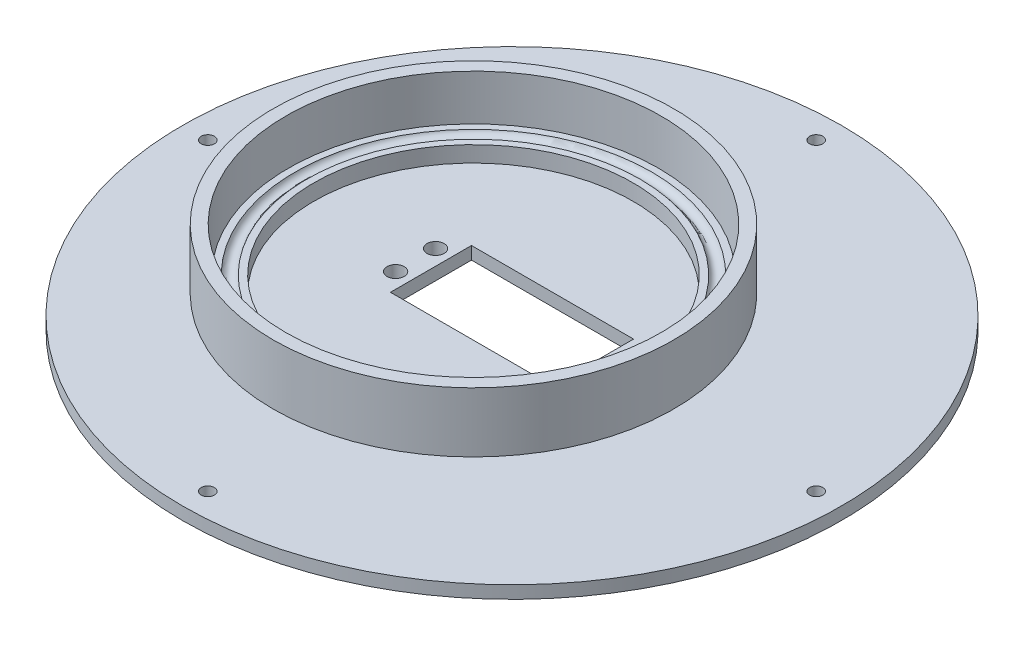
SolidWorks part; units mm, degrees
ref_plane "Front Plane" through (0, 0, 0) normal (0, 0, 1) x (1, 0, 0)
ref_plane "Top Plane" through (0, 0, 0) normal (0, 1, 0) x (1, 0, 0)
ref_plane "Right Plane" through (0, 0, 0) normal (1, 0, 0) x (0, 0, -1)
sketch "Sketch1" plane through (0, 0, 0) normal (0, 1, 0) x (1, 0, 0)
  circle A0 centre (0, 0) radius 82.55
  dimension "D1" = 165.1
extrude "Boss-Extrude1" add sketch "Sketch1" along normal blind 3.175 contours A0
sketch "Sketch2" plane through (0, 3.175, 0) normal (0, 1, 0) x (1, 0, 0)
  line L0 (-82.55, 0) -> (82.55, 0) construction
  line L5 (-24.15, 5) -> (24.15, 5) construction
  line L7 (-24.15, 5) -> (-24.15, -5) construction
  line L8 (-24.15, -5) -> (24.15, -5) construction
  line L9 (24.15, 5) -> (24.15, -5) construction
  line L10 (-24.15, 5) -> (24.15, -5) construction
  line L11 (-24.15, -5) -> (24.15, 5) construction
  line L13 (-20.3, 10.15) -> (20.3, 10.15)
  line L14 (-20.3, 10.15) -> (-20.3, -10.15)
  line L15 (-20.3, -10.15) -> (20.3, -10.15)
  line L16 (20.3, 10.15) -> (20.3, -10.15)
  line L17 (-20.3, 10.15) -> (20.3, -10.15) construction
  line L18 (-20.3, -10.15) -> (20.3, 10.15) construction
  circle A0 centre (-24.15, 5) radius 2.15
  circle A1 centre (-24.15, -5) radius 2.15
  circle A2 centre (24.15, 5) radius 2.15
  circle A3 centre (24.15, -5) radius 2.15
  circle A4 centre (0, 0) radius 82.55 construction
  point P1 (0, 0)
  point P14 (0, 0)
  dimension "D2" = 4.3
  dimension "D4" = 40.6
  dimension "D5" = 20.3
  dimension "D1" = 48.3
  dimension "D3" = 10
extrude "Cut-Extrude1" cut sketch "Sketch2" against normal blind 3.175
sketch "Sketch3" plane through (0, 3.175, 0) normal (0, 1, 0) x (1, 0, 0)
  line L0 (0, 0) -> (-82.55, 0) construction
  circle A0 centre (0, 0) radius 82.55 construction
  circle A1 centre (-76.2, 0) radius 1.65
  dimension "D2" = 3.3
  dimension "D3" = 76.2
  dimension "D1" = 82.55
extrude "Cut-Extrude2" cut sketch "Sketch3" against normal blind 3.175
pattern_circular "CirPattern1" count 4 over 360 about axis through (0, 0, 0) along (0, 1, 0) of "Cut-Extrude2"
sketch "Sketch4" plane through (0, 3.175, 0) normal (0, 1, 0) x (1, 0, 0)
  line L0 (0, 0) -> (-9.65, 0) construction
  circle A0 centre (-9.65, 0) radius 40
  circle A1 centre (-9.65, 0) radius 46.35
  dimension "D2" = 6.35
  dimension "D3" = 80
  dimension "D1" = 9.65
extrude "Boss-Extrude2" add sketch "Sketch4" along normal blind 4
sketch "Sketch7" plane through (0, 0, 0) normal (0, 0, 1) x (1, 0, 0)
  line L1 (-9.65, 3.175) -> (-9.65, 34.2214) construction
  line L2 (82.55, 3.175) -> (-82.55, 3.175) construction
  circle A0 centre (-52.825, 7.675) radius 1.5875
  dimension "D1" = 3.175
  dimension "D2" = 52.825
  dimension "D3" = 4.5
revolve "Cut-Revolve1" cut sketch "Sketch7" angle 360 about L1
sketch "Sketch8" plane through (0, 3.175, 0) normal (0, 1, 0) x (1, 0, 0)
  circle A0 centre (-9.65, 0) radius 47
  circle A1 centre (-9.65, 0) radius 50.175
  circle A2 centre (-9.65, 0) radius 46.35 construction
  dimension "D1" = 3.175
  dimension "D2" = 0.65
extrude "Boss-Extrude3" add sketch "Sketch8" along normal blind 15
